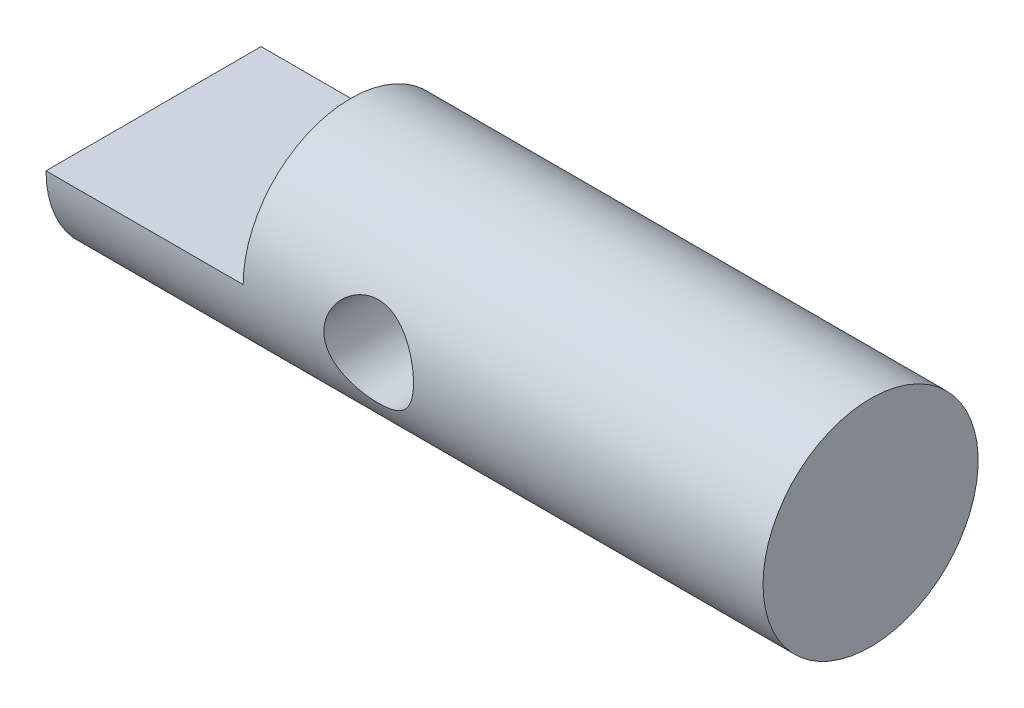
SolidWorks part; units mm, degrees
ref_plane "Ön Düzlem" through (0, 0, 0) normal (0, 0, 1) x (1, 0, 0)
ref_plane "Üst Düzlem" through (0, 0, 0) normal (0, 1, 0) x (1, 0, 0)
ref_plane "Sağ Düzlem" through (0, 0, 0) normal (1, 0, 0) x (0, 0, -1)
sketch "Sketch1" plane through (0, 0, 0) normal (0, 0, 1) x (1, 0, 0)
  line L1 (-8.9041, 4.0274) -> (11.0959, 4.0274)
  line L2 (-8.9041, 4.0274) -> (-8.9041, 1.0274)
  line L3 (-8.9041, 1.0274) -> (11.0959, 1.0274)
  line L4 (11.0959, 4.0274) -> (11.0959, 1.0274)
  dimension "D1" = 20
  dimension "D2" = 3
revolve "Revolve1" add sketch "Sketch1" angle 360 about L1
sketch "Sketch2" plane through (0, 0, 0) normal (0, 0, 1) x (1, 0, 0)
  line L0 (-8.9041, 4.0274) -> (-3.4041, 4.0274)
  line L1 (-8.9041, 7.0274) -> (-8.9041, 1.0274) construction
  line L2 (-3.4041, 4.0274) -> (-3.4041, 7.0274)
  line L3 (11.0959, 7.0274) -> (-8.9041, 7.0274) construction
  line L4 (-3.4041, 7.0274) -> (-8.9041, 7.0274)
  line L5 (-8.9041, 7.0274) -> (-8.9041, 4.0274)
  dimension "D1" = 5.5
extrude "Cut-Extrude1" cut sketch "Sketch2" against normal through all both and the other way through all
ref_plane "Plane1" through (0, 0, 3) normal (0, 0, 1) x (1, 0, 0)
sketch "Sketch4" plane through (0, 0, 3) normal (0, 0, 1) x (1, 0, 0)
  line L0 (-8.9041, 4.0274) -> (0.0959, 4.0274)
  circle A0 centre (0.0959, 4.0274) radius 1.25
  dimension "D2" = 2.5
  dimension "D1" = 9
extrude "Cut-Extrude2" cut sketch "Sketch4" against normal blind 3.2
